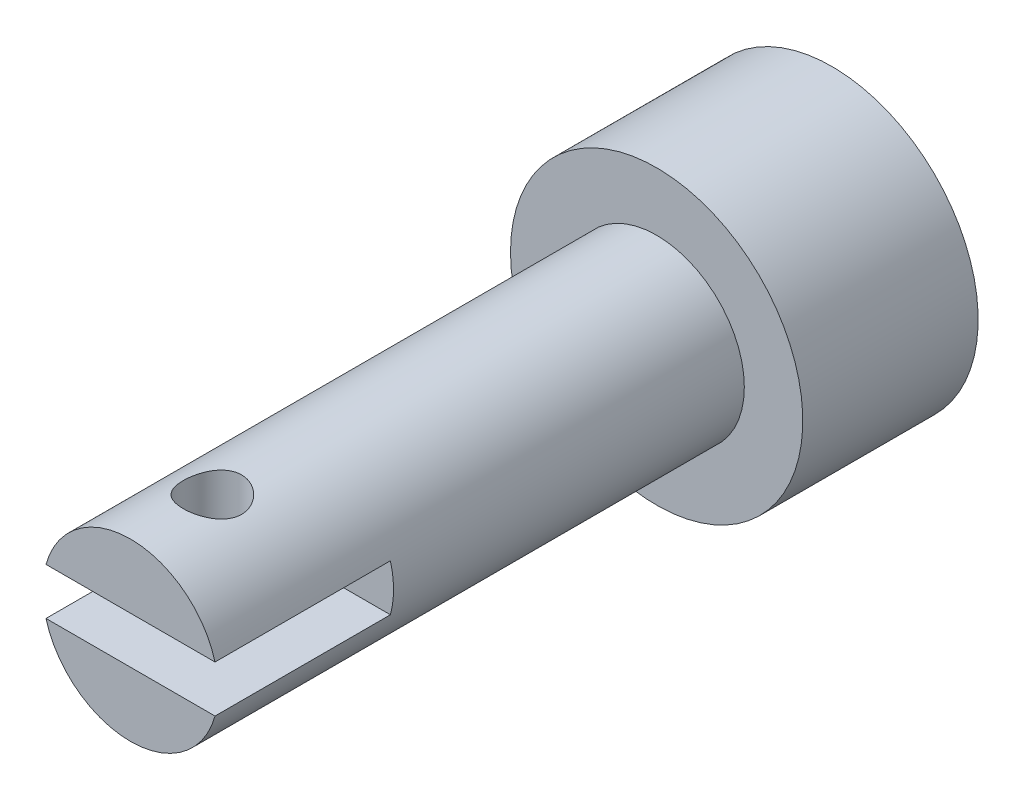
SolidWorks part; units mm, degrees
ref_plane "Front Plane" through (0, 0, 0) normal (0, 0, 1) x (1, 0, 0)
ref_plane "Top Plane" through (0, 0, 0) normal (0, 1, 0) x (1, 0, 0)
ref_plane "Right Plane" through (0, 0, 0) normal (1, 0, 0) x (0, 0, -1)
sketch "Sketch1" plane through (0, 0, 0) normal (0, 0, 1) x (1, 0, 0)
  circle A0 centre (0, 0) radius 7.5
  dimension "D1" = 15
extrude "Boss-Extrude1" add sketch "Sketch1" along normal mid plane 60
sketch "Sketch2" plane through (0, 0, 30) normal (0, 0, 1) x (1, 0, 0)
  line L1 (10, -2) -> (-10, -2)
  line L2 (10, -2) -> (10, 2)
  line L3 (10, 2) -> (-10, 2)
  line L4 (-10, -2) -> (-10, 2)
  line L5 (10, -2) -> (-10, 2) construction
  line L6 (10, 2) -> (-10, -2) construction
  point P0 (0, 0)
  point P6 (7.288, 0.5317)
  dimension "D1" = 4
  dimension "D2" = 20
extrude "Cut-Extrude1" cut sketch "Sketch2" against normal blind 15
sketch "Sketch3" plane through (0, 0, 0) normal (0, 1, 0) x (1, 0, 0)
  line L0 (-7.2284, -30) -> (7.2284, -30) construction
  circle A0 centre (0, -23) radius 2.5
  dimension "D1" = 5
  dimension "D2" = 7
extrude "Cut-Extrude2" cut sketch "Sketch3" against normal mid plane 15
sketch "Sketch4" plane through (0, 0, -30) normal (0, 0, -1) x (-1, 0, 0)
  circle A0 centre (0, 0) radius 12.5
  dimension "D1" = 25
extrude "Boss-Extrude2" add sketch "Sketch4" against normal blind 15
